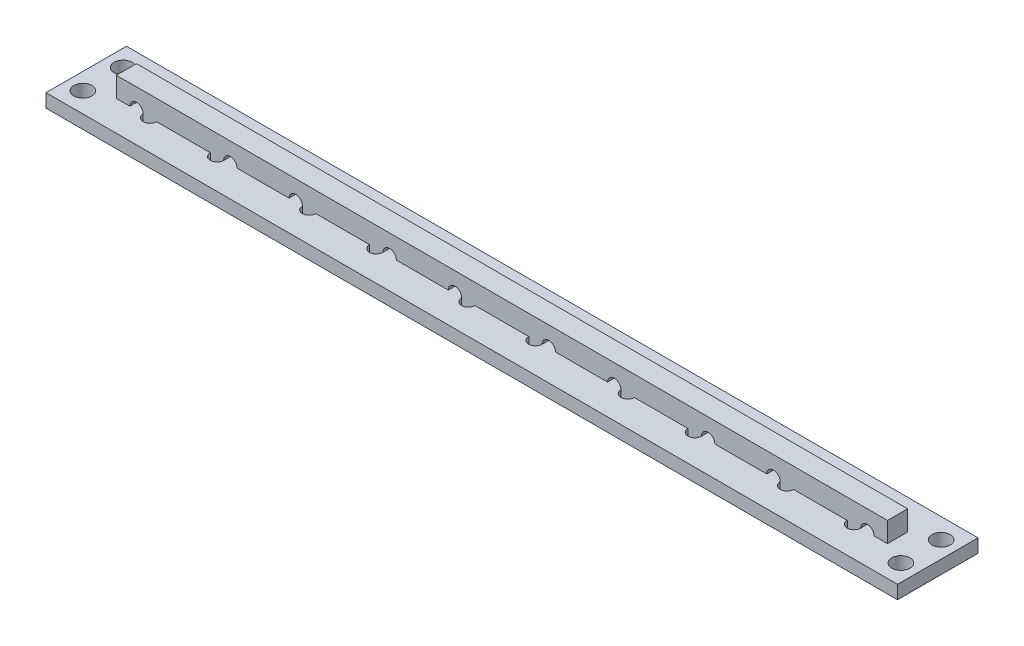
SolidWorks part; units mm, degrees
material "碳纤维"
ref_plane "前视基准面" through (0, 0, 0) normal (0, 0, 1) x (1, 0, 0)
ref_plane "上视基准面" through (0, 0, 0) normal (0, 1, 0) x (1, 0, 0)
ref_plane "右视基准面" through (0, 0, 0) normal (1, 0, 0) x (0, 0, -1)
sketch "草图1" plane through (0, 0, 0) normal (0, 1, 0) x (1, 0, 0)
  line L0 (63.5, 12) -> (63.5, 0) construction
  line L1 (0, 0) -> (127, 0)
  line L2 (0, 0) -> (0, 12)
  line L3 (0, 12) -> (127, 12)
  line L4 (127, 0) -> (127, 12)
  line L5 (0, 6) -> (127, 6) construction
  line L6 (2.5, 9) -> (2.5, 3) construction
  line L7 (10, 7.5) -> (12, 7.5) construction
  line L8 (12, 7.5) -> (20, 7.5)
  line L9 (10, 7.5) -> (10, 4.5)
  line L10 (12, 4.5) -> (20, 4.5)
  line L11 (22, 7.5) -> (22, 4.5)
  line L12 (20, 4.5) -> (22, 4.5) construction
  line L13 (12, 4.5) -> (10, 4.5) construction
  line L14 (20, 7.5) -> (22, 7.5) construction
  line L15 (35.75, 4.5) -> (43.75, 4.5)
  line L16 (33.75, 7.5) -> (33.75, 4.5)
  line L17 (35.75, 7.5) -> (43.75, 7.5)
  line L18 (45.75, 7.5) -> (45.75, 4.5)
  line L19 (59.5, 4.5) -> (67.5, 4.5)
  line L20 (57.5, 7.5) -> (57.5, 4.5)
  line L21 (59.5, 7.5) -> (67.5, 7.5)
  line L22 (69.5, 7.5) -> (69.5, 4.5)
  line L23 (83.25, 4.5) -> (91.25, 4.5)
  line L24 (81.25, 7.5) -> (81.25, 4.5)
  line L25 (83.25, 7.5) -> (91.25, 7.5)
  line L26 (93.25, 7.5) -> (93.25, 4.5)
  line L27 (107, 4.5) -> (115, 4.5)
  line L28 (105, 7.5) -> (105, 4.5)
  line L29 (107, 7.5) -> (115, 7.5)
  line L30 (117, 7.5) -> (117, 4.5)
  arc A5 (12, 7.5) -> (10, 7.5) centre (11, 7.5) ccw
  arc A6 (22, 7.5) -> (20, 7.5) centre (21, 7.5) ccw
  arc A7 (12, 4.5) -> (10, 4.5) centre (11, 4.5) cw
  arc A8 (22, 4.5) -> (20, 4.5) centre (21, 4.5) cw
  arc A9 (45.75, 4.5) -> (43.75, 4.5) centre (44.75, 4.5) cw
  arc A10 (35.75, 4.5) -> (33.75, 4.5) centre (34.75, 4.5) cw
  arc A11 (35.75, 7.5) -> (33.75, 7.5) centre (34.75, 7.5) ccw
  arc A12 (45.75, 7.5) -> (43.75, 7.5) centre (44.75, 7.5) ccw
  arc A13 (69.5, 4.5) -> (67.5, 4.5) centre (68.5, 4.5) cw
  arc A14 (59.5, 4.5) -> (57.5, 4.5) centre (58.5, 4.5) cw
  arc A15 (59.5, 7.5) -> (57.5, 7.5) centre (58.5, 7.5) ccw
  arc A16 (69.5, 7.5) -> (67.5, 7.5) centre (68.5, 7.5) ccw
  arc A17 (93.25, 4.5) -> (91.25, 4.5) centre (92.25, 4.5) cw
  arc A18 (83.25, 4.5) -> (81.25, 4.5) centre (82.25, 4.5) cw
  arc A19 (83.25, 7.5) -> (81.25, 7.5) centre (82.25, 7.5) ccw
  arc A20 (93.25, 7.5) -> (91.25, 7.5) centre (92.25, 7.5) ccw
  arc A21 (117, 4.5) -> (115, 4.5) centre (116, 4.5) cw
  arc A22 (107, 4.5) -> (105, 4.5) centre (106, 4.5) cw
  arc A23 (107, 7.5) -> (105, 7.5) centre (106, 7.5) ccw
  arc A24 (117, 7.5) -> (115, 7.5) centre (116, 7.5) ccw
  circle A25 centre (2.5, 9) radius 1.35
  circle A26 centre (2.5, 3) radius 1.35
  circle A27 centre (124.5, 3) radius 1.35
  circle A28 centre (124.5, 9) radius 1.35
  point P23 (10, 6)
  dimension "D2" = 2.7
  dimension "D3" = 12
  dimension "D4" = 6
  dimension "D8" = 2
  dimension "D1" = 127
  dimension "D5" = 2.5
  dimension "D6" = 12
  dimension "D7" = 3
  dimension "D10" = 10
  dimension "D11" = 10
  dimension "D9" = 5
extrude "凸台-拉伸1" add sketch "草图1" along normal blind 2
sketch "草图2" plane through (0, 0, -7.5) normal (0, 0, 1) x (1, 0, 0)
  line L2 (22, 0) -> (22, 2) construction
  line L52 (10, 2) -> (10, 0) construction
  line L54 (22, 0) -> (22, 2)
  line L60 (10, 2) -> (10, 0)
  line L61 (0, 2) -> (127, 2) construction
  line L62 (6, 2) -> (8, 2)
  line L63 (6, 2) -> (6, 5)
  line L64 (6, 5) -> (121, 5)
  line L65 (121, 2) -> (121, 5)
  line L66 (0, 2) -> (0, 0) construction
  line L67 (127, 2) -> (127, 0) construction
  line L68 (10, 0) -> (10, -2)
  line L69 (10, -2) -> (22, -2)
  line L70 (22, -2) -> (22, 0)
  line L71 (24, 2) -> (31.75, 2)
  line L72 (33.75, 2) -> (33.75, 0)
  line L73 (33.75, 0) -> (33.75, -2)
  line L74 (33.75, -2) -> (45.75, -2)
  line L75 (45.75, -2) -> (45.75, 0)
  line L76 (45.75, 0) -> (45.75, 2)
  line L77 (57.5, 2) -> (57.5, 0)
  line L78 (57.5, 0) -> (57.5, -2)
  line L79 (57.5, -2) -> (69.5, -2)
  line L80 (69.5, -2) -> (69.5, 0)
  line L81 (69.5, 0) -> (69.5, 2)
  line L82 (81.25, 2) -> (81.25, 0)
  line L83 (81.25, 0) -> (81.25, -2)
  line L84 (81.25, -2) -> (93.25, -2)
  line L85 (93.25, -2) -> (93.25, 0)
  line L86 (93.25, 0) -> (93.25, 2)
  line L87 (105, 2) -> (105, 0)
  line L88 (105, 0) -> (105, -2)
  line L89 (105, -2) -> (117, -2)
  line L90 (117, -2) -> (117, 0)
  line L91 (117, 0) -> (117, 2)
  line L92 (47.75, 2) -> (55.5, 2)
  line L93 (71.5, 2) -> (79.25, 2)
  line L94 (95.25, 2) -> (103, 2)
  line L95 (119, 2) -> (121, 2)
  arc A10 (10, 2) -> (8, 2) centre (9, 2) ccw
  arc A11 (24, 2) -> (22, 2) centre (23, 2) ccw
  arc A12 (33.75, 2) -> (31.75, 2) centre (32.75, 2) ccw
  arc A13 (47.75, 2) -> (45.75, 2) centre (46.75, 2) ccw
  arc A14 (57.5, 2) -> (55.5, 2) centre (56.5, 2) ccw
  arc A15 (71.5, 2) -> (69.5, 2) centre (70.5, 2) ccw
  arc A16 (81.25, 2) -> (79.25, 2) centre (80.25, 2) ccw
  arc A17 (95.25, 2) -> (93.25, 2) centre (94.25, 2) ccw
  arc A18 (105, 2) -> (103, 2) centre (104, 2) ccw
  arc A19 (119, 2) -> (117, 2) centre (118, 2) ccw
  dimension "D4" = 2
  dimension "D1" = 6
  dimension "D2" = 6
  dimension "D3" = 2
  dimension "D5" = 5
  dimension "D7" = 3
  dimension "D6" = 10
extrude "凸台-拉伸2" add sketch "草图2" along normal blind 3 separate body
